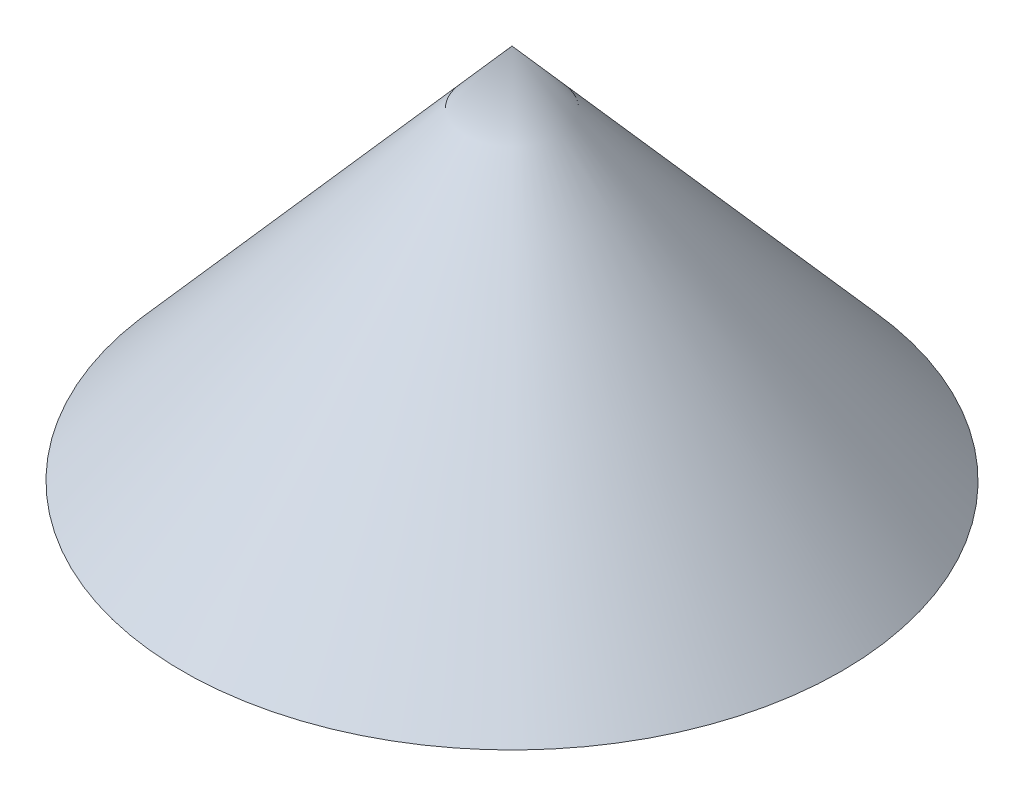
SolidWorks part; units mm, degrees
material "Prata-níquel 65-12, UNS C75700"
ref_plane "Plano frontal" through (0, 0, 0) normal (0, 0, 1) x (1, 0, 0)
ref_plane "Plano superior" through (0, 0, 0) normal (0, 1, 0) x (1, 0, 0)
ref_plane "Plano direito" through (0, 0, 0) normal (1, 0, 0) x (0, 0, -1)
sketch "Esboço1" plane through (0, 0, 0) normal (0, 0, 1) x (1, 0, 0)
  line L0 (0, 0) -> (-0.7, 0)
  line L1 (-0.7, 0) -> (0, 0.8)
  line L2 (0, 0.8) -> (0, 0)
  dimension "D1" = 0.7
  dimension "D2" = 0.8
revolve "Revolução1" add sketch "Esboço1" angle 360 about L2
